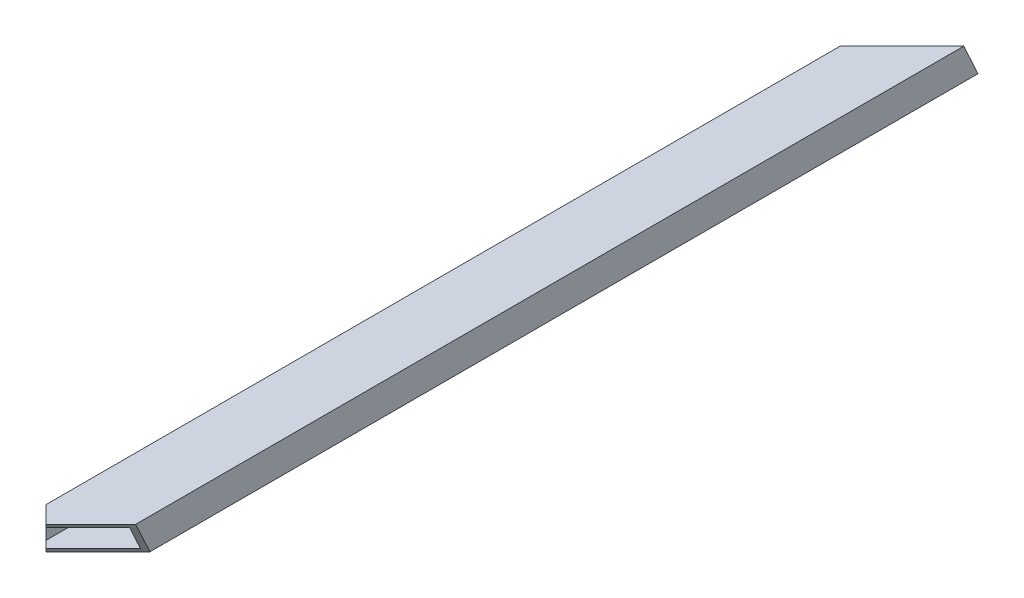
SolidWorks part; units mm, degrees
ref_plane "Front Plane" through (0, 0, 0) normal (0, 0, 1) x (1, 0, 0)
ref_plane "Top Plane" through (0, 0, 0) normal (0, 1, 0) x (1, 0, 0)
ref_plane "Right Plane" through (0, 0, 0) normal (1, 0, 0) x (0, 0, -1)
sketch "Sketch1" plane through (0, 0, 0) normal (0, 0, 1) x (1, 0, 0)
  line L0 (-22.225, 9.525) -> (22.225, 9.525)
  line L1 (-25.4, -12.7) -> (25.4, -12.7)
  line L2 (-25.4, -12.7) -> (-25.4, 12.7)
  line L3 (-25.4, 12.7) -> (25.4, 12.7)
  line L4 (25.4, -12.7) -> (25.4, 12.7)
  line L5 (-25.4, -12.7) -> (25.4, 12.7) construction
  line L6 (-25.4, 12.7) -> (25.4, -12.7) construction
  line L7 (22.225, -9.525) -> (22.225, 9.525)
  line L8 (-22.225, -9.525) -> (22.225, -9.525)
  line L9 (-22.225, -9.525) -> (-22.225, 9.525)
  point P0 (0, 0)
  dimension "D1" = 25.4
  dimension "D2" = 50.8
  dimension "D3" = 3.175
extrude "Boss-Extrude1" add sketch "Sketch1" along normal blind 771.9314
sketch "Sketch2" plane through (0, 12.7, 0) normal (0, 1, 0) x (1, 0, 0)
  line L0 (25.4, 0) -> (-25.4, -50.8)
  line L1 (-25.4, -771.9314) -> (-25.4, 0) construction
  line L2 (-25.4, -50.8) -> (-25.4, 0)
  line L3 (-25.4, 0) -> (25.4, 0)
  line L4 (-25.4, -771.9314) -> (25.4, -721.1314)
  line L5 (25.4, -771.9314) -> (25.4, 0) construction
  line L6 (25.4, -721.1314) -> (25.4, -771.9314)
  line L7 (25.4, -771.9314) -> (-25.4, -771.9314)
  dimension "D1" = 45
  dimension "D2" = 45
extrude "Cut-Extrude1" cut sketch "Sketch2" against normal through all
ref_plane "Plane5" through (-369.8785, 0, 369.8785) normal (0.7071, 0, -0.7071) x (-0.7071, 0, -0.7071)
sketch "Sketch10" plane through (-369.8785, 0, 369.8785) normal (0.7071, 0, -0.7071) x (-0.7071, 0, -0.7071)
  line L1 (-539.6206, -41.2775) -> (-449.2638, -41.2775)
  line L2 (-539.6206, -41.2775) -> (-539.6206, 88.6294)
  line L3 (-539.6206, 88.6294) -> (-449.2638, 88.6294)
  line L4 (-449.2638, -41.2775) -> (-449.2638, 88.6294)
extrude "Cut-Extrude8" cut sketch "Sketch10" against normal blind 40.64
ref_plane "Plane6" through (386.2591, 0, -386.2591) normal (0.7071, 0, -0.7071) x (-0.7071, 0, -0.7071)
sketch "Sketch11" plane through (386.2591, 0, -386.2591) normal (0.7071, 0, -0.7071) x (-0.7071, 0, -0.7071)
  line L0 (-17.9605, -12.7) -> (-26.2135, 12.7)
  line L1 (-527.8774, 12.7) -> (-17.9605, 12.7) construction
  line L2 (-26.2135, 12.7) -> (-17.9605, 12.7)
  line L3 (-17.9605, 12.7) -> (-17.9605, -12.7)
  dimension "D1" = 18
extrude "Cut-Extrude9" cut sketch "Sketch11" against normal through all
ref_plane "Plane7" through (-332.1614, 0, 332.1614) normal (0.7071, 0, -0.7071) x (-0.7071, 0, -0.7071)
sketch "Sketch12" plane through (-332.1614, 0, 332.1614) normal (0.7071, 0, -0.7071) x (-0.7071, 0, -0.7071)
  line L0 (-498.689, -12.7) -> (-506.942, 12.7)
  line L1 (-527.8774, -12.7) -> (-17.9605, -12.7) construction
  line L2 (-519.0969, 50.109) -> (-362.1163, -433.0277) construction
  line L3 (-527.8774, 12.7) -> (-26.2135, 12.7) construction
  line L4 (-506.942, 12.7) -> (-527.8774, 12.7)
  line L5 (-527.8774, 12.7) -> (-527.8774, -12.7)
  line L6 (-527.8774, -12.7) -> (-498.689, -12.7)
extrude "Cut-Extrude10" cut sketch "Sketch12" against normal through all both and the other way through all
